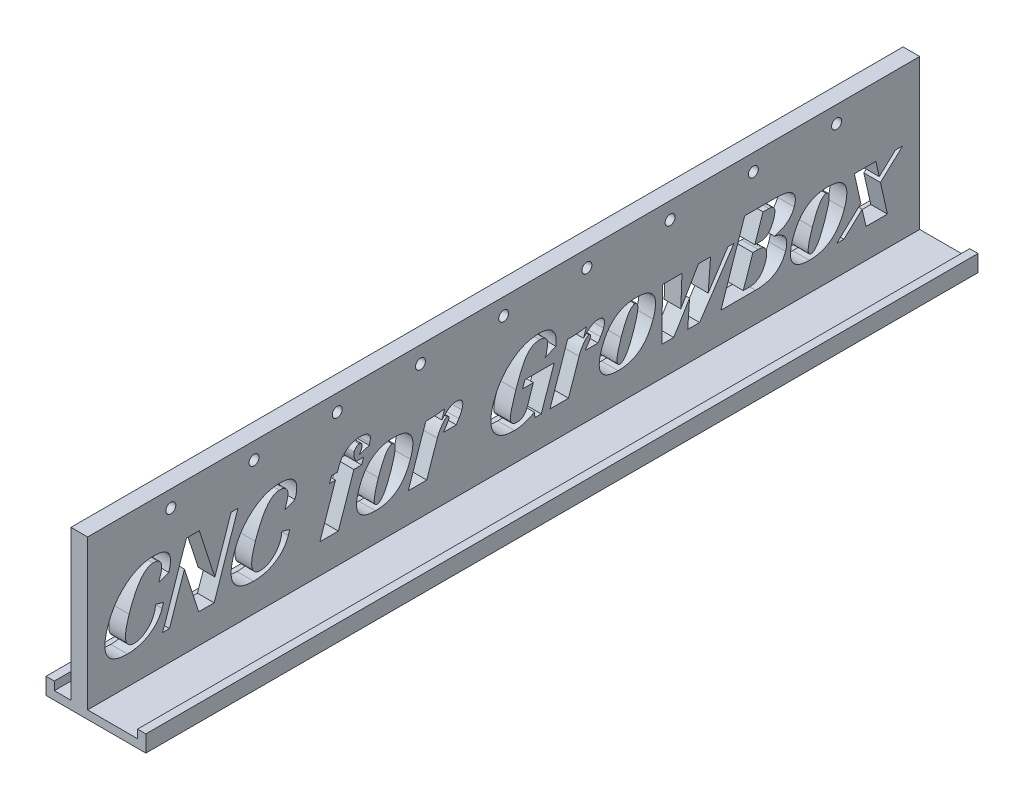
SolidWorks part; units mm, degrees
material "Acrylic (Medium-high impact)"
ref_plane "Front Plane" through (0, 0, 0) normal (0, 0, 1) x (1, 0, 0)
ref_plane "Top Plane" through (0, 0, 0) normal (0, 1, 0) x (1, 0, 0)
ref_plane "Right Plane" through (0, 0, 0) normal (1, 0, 0) x (0, 0, -1)
sketch "Sketch1" plane through (0, 0, 0) normal (0, 0, 1) x (1, 0, 0)
  line L0 (0, 10) -> (0, 0)
  line L1 (0, 0) -> (60, 0)
  line L2 (60, 0) -> (60, 10)
  line L3 (60, 10) -> (55, 10)
  line L4 (55, 10) -> (55, 5)
  line L5 (55, 5) -> (25, 5)
  line L6 (25, 5) -> (25, 95)
  line L7 (25, 95) -> (15, 95)
  line L8 (15, 95) -> (15, 5)
  line L9 (15, 5) -> (5, 5)
  line L10 (5, 5) -> (5, 10)
  line L11 (5, 10) -> (0, 10)
  dimension "D1" = 10
  dimension "D2" = 10
  dimension "D3" = 5
  dimension "D4" = 5
  dimension "D5" = 5
  dimension "D6" = 10
  dimension "D7" = 60
  dimension "D8" = 95
  dimension "D9" = 5
extrude "Boss-Extrude1" add sketch "Sketch1" along normal blind 500
sketch "Sketch2" plane through (25, 0, 0) normal (1, 0, 0) x (0, 0, -1)
  line L0 (-1052.1126, 85) -> (45.5589, 85) construction
  line L1 (-500, 95) -> (-475, 95)
  line L2 (-500, 95) -> (-500, 70)
  line L3 (-500, 70) -> (-475, 70)
  line L4 (-475, 95) -> (-475, 70)
  line L5 (0, 95) -> (-25, 95)
  line L6 (0, 95) -> (0, 70)
  line L7 (0, 70) -> (-25, 70)
  line L8 (-25, 95) -> (-25, 70)
  line L9 (-500, 95) -> (0, 95) construction
  dimension "D1" = 25
  dimension "D2" = 25
  dimension "D3" = 25
  dimension "D4" = 25
  dimension "D5" = 10
extrude "Cut-Extrude1" [suppressed] cut sketch "Sketch2" against normal blind 10
sketch "Sketch3" [suppressed] plane through (25, 0, 0) normal (1, 0, 0) x (0, 0, -1)
  line L0 (-995, 70) -> (-995, 95) construction
  line L1 (-995, 95) -> (-25, 95) construction
  circle A0 centre (-898, 85) radius 3
  dimension "D3" = 6
  dimension "D1" = 97
  dimension "D2" = 10
extrude "Cut-Extrude2" [suppressed] cut sketch "Sketch3" against normal blind 10
pattern_linear "LPattern1" [suppressed] count 9 spacing 97
ref_plane "Plane1" through (0, 0, 250) normal (0, 0, -1) x (-1, 0, 0)
sketch "Sketch4" plane through (25, 0, 0) normal (1, 0, 0) x (0, 0, -1)
  line L0 (-500, 95) -> (0, 95) construction
  line L2 (-500, 5) -> (-500, 95) construction
  circle A0 centre (-450, 85) radius 3
  dimension "D2" = 6
  dimension "D1" = 10
  dimension "D3" = 50
extrude "Cut-Extrude3" cut sketch "Sketch4" against normal blind 10
pattern_linear "LPattern2" count 9 spacing 50 along (0, 0, -1) of "Cut-Extrude3"
sketch "Sketch5" plane through (25, 0, 0) normal (1, 0, 0) x (0, 0, -1)
  text T0 "CNC for GrowBox" font "Britannic Bold" height 42
extrude "Cut-Extrude4" cut sketch "Sketch5" against normal blind 10
